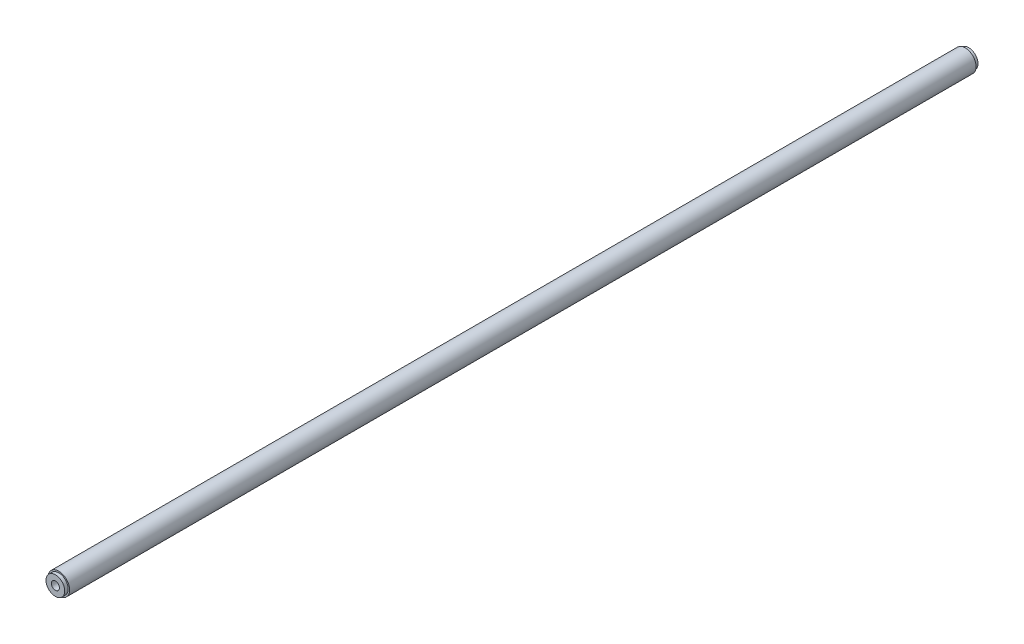
SolidWorks part; units mm, degrees
material "Alloy Steel"
ref_plane "Front Plane" through (0, 0, 0) normal (0, 0, 1) x (1, 0, 0)
ref_plane "Top Plane" through (0, 0, 0) normal (0, 1, 0) x (1, 0, 0)
ref_plane "Right Plane" through (0, 0, 0) normal (1, 0, 0) x (0, 0, -1)
sketch "Sketch1" plane through (0, 0, 0) normal (0, 0, 1) x (1, 0, 0)
  circle A0 centre (0, 0) radius 6.35
  dimension "D1" = 12.7
extrude "Boss-Extrude1" add sketch "Sketch1" along normal blind 531
sketch "Sketch2" plane through (0, 0, 531) normal (0, 0, 1) x (1, 0, 0)
  circle A0 centre (0, 0) radius 5.5
  dimension "D1" = 11
extrude "Boss-Extrude2" add sketch "Sketch2" along normal blind 2
sketch "Sketch3" plane through (0, 0, 0) normal (0, 0, -1) x (-1, 0, 0)
  circle A0 centre (0, 0) radius 5.5
  dimension "D1" = 11
extrude "Boss-Extrude3" add sketch "Sketch3" along normal blind 2
sketch "Sketch4" plane through (0, 0, -2) normal (0, 0, -1) x (-1, 0, 0)
  circle A0 centre (0, 0) radius 2.375
  dimension "D1" = 4.75
extrude "Cut-Extrude1" cut sketch "Sketch4" against normal through all both and the other way through all
